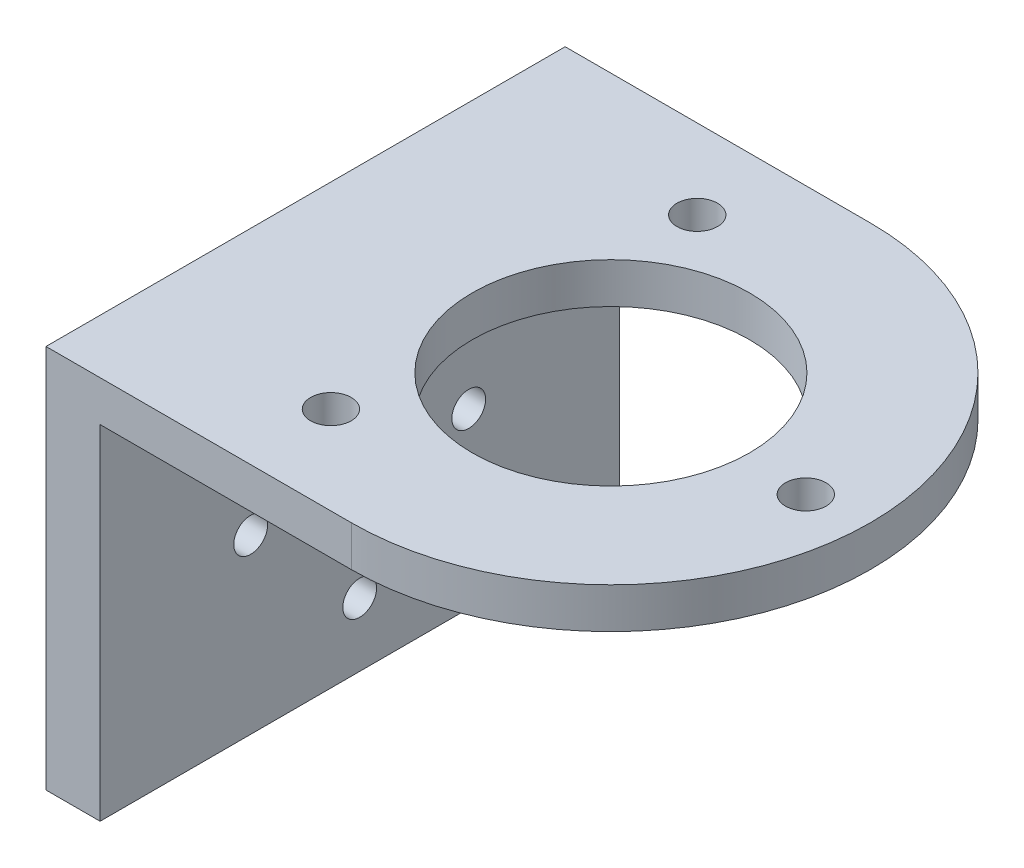
SolidWorks part; units mm, degrees
ref_plane "Front Plane" through (0, 0, 0) normal (0, 0, 1) x (1, 0, 0)
ref_plane "Top Plane" through (0, 0, 0) normal (0, 1, 0) x (1, 0, 0)
ref_plane "Right Plane" through (0, 0, 0) normal (1, 0, 0) x (0, 0, -1)
sketch "Sketch1" plane through (0, 0, 0) normal (0, 1, 0) x (1, 0, 0)
  line L22 (0, 19.19) -> (-22.5713, 19.19)
  line L23 (0, 19.19) -> (0, -19.19)
  line L24 (0, -19.19) -> (-22.5713, -19.19)
  line L25 (-22.5713, 19.19) -> (-22.5713, -19.19)
  circle A0 centre (0, 0) radius 19.19
  circle A1 centre (0, 0) radius 10.25
  arc A6 (-9.2547, -11.8047) -> (-6.7239, -13.4085) centre (0, 0) ccw
  circle A7 centre (-6.9236, 13.3065) radius 1.5
  circle A8 centre (14.9888, -0.5803) radius 1.5
  circle A9 centre (-8.0295, -12.67) radius 1.5
  circle A10 centre (0, 0) radius 10.25
  dimension "D1" = 30
  dimension "D3" = 20.5
  dimension "D4" = 38.38
  dimension "D2" = 26
  dimension "D6" = 25.9422
  dimension "D5" = 26
extrude "Boss-Extrude3" add sketch "Sketch1" along normal blind 3 contours A1 L23 A0 A9 A7 | A1 L23 A0 A8 | L23 A1 | L23 A1 | A0 L22 L25 L24
sketch "Sketch2" plane through (0, 0, 0) normal (0, -1, 0) x (1, 0, 0)
  line L0 (0, -19.19) -> (-22.5713, -19.19) construction
  line L1 (-22.5713, 19.19) -> (-18.5713, 19.19)
  line L2 (-22.5713, 19.19) -> (-22.5713, -19.19)
  line L3 (-22.5713, -19.19) -> (-18.5713, -19.19)
  line L4 (-18.5713, 19.19) -> (-18.5713, -19.19)
  dimension "D1" = 4
extrude "Boss-Extrude4" add sketch "Sketch2" along normal blind 25.4
sketch "Sketch3" plane through (-18.5713, 0, 0) normal (1, 0, 0) x (0, 0, -1)
  line L0 (-19.19, -25.4) -> (-19.19, 0) construction
  line L2 (0, -4.5635) -> (0, -20.6835)
  line L3 (-8.06, -12.6235) -> (8.06, -12.6235)
  circle A0 centre (0, -12.6235) radius 10.95
  circle A1 centre (0, -12.6235) radius 8.06
  circle A2 centre (0, -4.5635) radius 1.25
  circle A3 centre (-8.06, -12.6235) radius 1.25
  circle A4 centre (0, -20.6835) radius 1.25
  circle A5 centre (8.06, -12.6235) radius 1.25
  dimension "D1" = 19.19
extrude "Cut-Extrude2" cut sketch "Sketch3" against normal blind 25.4 contours L3 A3 A1 | A1 A3 L3 | A1 A3 | L2 A4 A1 | A1 A4 L2 | A1 A4 | L3 A5 A1 | A1 A5 L3 | A1 A5 | L2 A2 A1 | A1 A2 L2 | A1 A2
